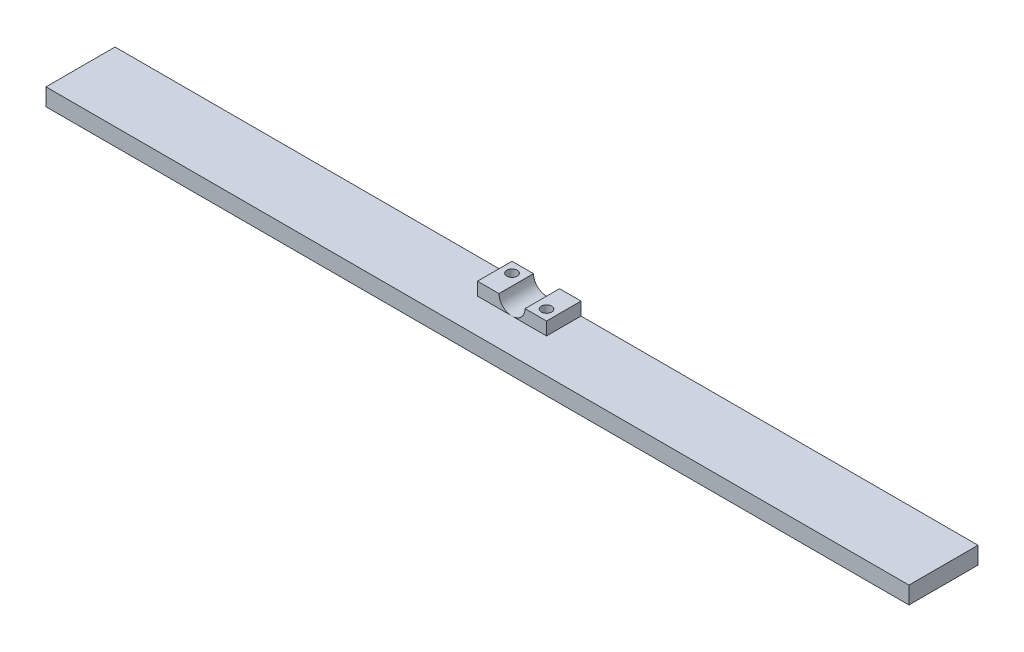
SolidWorks part; units mm, degrees
ref_plane "Front Plane" through (0, 0, 0) normal (0, 0, 1) x (1, 0, 0)
ref_plane "Top Plane" through (0, 0, 0) normal (0, 1, 0) x (1, 0, 0)
ref_plane "Right Plane" through (0, 0, 0) normal (1, 0, 0) x (0, 0, -1)
sketch "Sketch1" plane through (0, 0, 0) normal (0, 1, 0) x (1, 0, 0)
  line L1 (-42.9222, 6.7264) -> (207.0778, 6.7264)
  line L2 (-42.9222, 6.7264) -> (-42.9222, -13.2736)
  line L3 (-42.9222, -13.2736) -> (207.0778, -13.2736)
  line L4 (207.0778, 6.7264) -> (207.0778, -13.2736)
  dimension "D1" = 250
  dimension "D2" = 20
extrude "Boss-Extrude1" add sketch "Sketch1" along normal blind 5
sketch "Sketch2" plane through (0, 5, 0) normal (0, 1, 0) x (1, 0, 0)
  line L0 (207.0778, 6.7264) -> (-42.9222, 6.7264) construction
  line L1 (72.0778, 6.7264) -> (92.0778, 6.7264)
  line L2 (72.0778, 6.7264) -> (72.0778, -3.2736)
  line L3 (72.0778, -3.2736) -> (92.0778, -3.2736)
  line L4 (92.0778, 6.7264) -> (92.0778, -3.2736)
  line L5 (207.0778, -13.2736) -> (207.0778, 6.7264) construction
  dimension "D1" = 20
  dimension "D2" = 10
  dimension "D3" = 115
extrude "Boss-Extrude2" add sketch "Sketch2" along normal blind 3.75
sketch "Sketch3" plane through (0, 0, 3.2736) normal (0, 0, 1) x (1, 0, 0)
  line L0 (72.0778, 8.75) -> (92.0778, 8.75) construction
  line L1 (92.0778, 8.75) -> (92.0778, 5) construction
  circle A0 centre (82.0778, 8.75) radius 3.775
  dimension "D1" = 7.55
  dimension "D2" = 10
extrude "Cut-Extrude1" cut sketch "Sketch3" against normal blind 10
sketch "Sketch4" plane through (0, 8.75, 0) normal (0, 1, 0) x (1, 0, 0)
  line L0 (78.3028, 6.7264) -> (72.0778, 6.7264) construction
  line L1 (72.0778, 6.7264) -> (72.0778, -3.2736) construction
  line L3 (92.0778, -3.2736) -> (92.0778, 6.7264) construction
  line L4 (85.8528, -3.2736) -> (92.0778, -3.2736) construction
  circle A0 centre (89.0778, -0.2736) radius 1.5
  circle A2 centre (75.0778, 3.7264) radius 1.5
  dimension "D1" = 3
  dimension "D2" = 3
  dimension "D3" = 3
  dimension "D4" = 3
  dimension "D5" = 3
  dimension "D6" = 3
extrude "Cut-Extrude2" cut sketch "Sketch4" against normal blind 4
